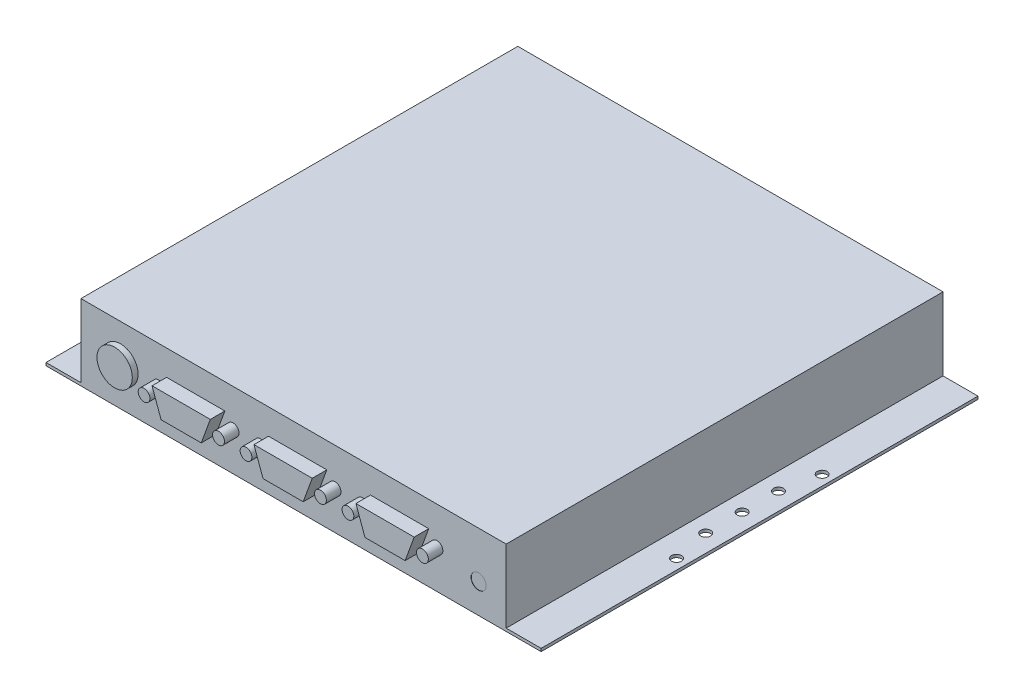
SolidWorks part; units mm, degrees
ref_plane "前视基准面" through (0, 0, 0) normal (0, 0, 1) x (1, 0, 0)
ref_plane "上视基准面" through (0, 0, 0) normal (0, 1, 0) x (1, 0, 0)
ref_plane "右视基准面" through (0, 0, 0) normal (1, 0, 0) x (0, 0, -1)
sketch "草图1" plane through (0, 0, 0) normal (0, 1, 0) x (1, 0, 0)
  line L1 (73, -75) -> (-73, -75)
  line L2 (73, -75) -> (73, 75)
  line L3 (73, 75) -> (-73, 75)
  line L4 (-73, -75) -> (-73, 75)
  line L5 (73, -75) -> (-73, 75) construction
  line L6 (73, 75) -> (-73, -75) construction
  point P0 (0, 0)
  dimension "D1" = 146
  dimension "D2" = 150
extrude "凸台-拉伸1" add sketch "草图1" along normal blind 26
sketch "草图2" plane through (0, 0, 0) normal (0, -1, 0) x (1, 0, 0)
  line L0 (-73, 75) -> (73, 75) construction
  line L1 (85, -75) -> (-85, -75)
  line L2 (85, -75) -> (85, 75)
  line L3 (85, 75) -> (-85, 75)
  line L4 (-85, -75) -> (-85, 75)
  line L5 (85, -75) -> (-85, 75) construction
  line L6 (85, 75) -> (-85, -75) construction
  point P0 (0, 0)
  dimension "D1" = 170
extrude "凸台-拉伸2" add sketch "草图2" against normal blind 1
hole_wizard "M3 间隙孔1" positions "草图3" profile "草图4" hole size "M3" standard "GB" end condition up to next
sketch "草图3" plane through (0, 1, 0) normal (0, 1, 0) x (1, 0, 0)
  line L0 (0, 0) -> (-85, 0) construction
  line L1 (-85, -75) -> (-85, 75) construction
  line L3 (0, 0) -> (0, 28.3891) construction
  line L6 (-73, -5.9635) -> (-85, -5.9635) construction
  line L7 (-73, -75) -> (-73, 75) construction
  point P0 (-81.5, 25)
  point P2 (-81.5, -25)
  point P4 (81.5, 25)
  point P6 (81.5, -25)
  point P19 (-79, 12.5)
  point P21 (-79, 0)
  point P23 (-79, -12.5)
  point P25 (79, -12.5)
  point P26 (79, 0)
  point P27 (79, 12.5)
  point P41 (-79, -5.9635)
  dimension "D1" = 163
  dimension "D2" = 50
  dimension "D3" = 25
sketch "草图4" plane through (-81.5, 1, -25) normal (1, 0, 0) x (0, 0, 1)
  line L0 (0, 0) -> (0, 1)
  line L1 (0, 1) -> (1.7, 1)
  line L2 (1.7, 1) -> (1.7, 0)
  line L5 (1.7, 0) -> (0, 0)
  line L11 (0, -6.35) -> (0, 107.95) construction
  dimension "通孔孔直径" = 3.4
  dimension "通孔孔深度" = 1
sketch "草图5" plane through (0, 0, 75) normal (0, 0, 1) x (1, 0, 0)
  circle A0 centre (-59.4316, 13.2786) radius 6.0638
extrude "凸台-拉伸3" add sketch "草图5" along normal blind 2
sketch "草图6" plane through (0, 0, 75) normal (0, 0, 1) x (1, 0, 0)
  line L0 (-43.5901, 17.274) -> (-23.5901, 17.274)
  line L1 (-23.5901, 17.274) -> (-26.6961, 8.7247)
  line L2 (-26.6961, 8.7247) -> (-40.484, 8.7247)
  line L3 (-40.484, 8.7247) -> (-43.5901, 17.274)
  line L4 (-33.5901, 8.7247) -> (-33.5901, 17.274) construction
  circle A0 centre (-46.3288, 13.1149) radius 2.0177
  circle A1 centre (-20.7695, 13.1149) radius 2.0399
  dimension "D1" = 20
extrude "凸台-拉伸4" add sketch "草图6" along normal blind 5
pattern_linear "阵列(线性)1" count 3 spacing 35 along (1, 0, 0) of "凸台-拉伸4"
sketch "草图7" plane through (0, 0, 75) normal (0, 0, 1) x (1, 0, 0)
  circle A0 centre (63.5175, 10.1213) radius 2.6001
extrude "切除-拉伸1" cut sketch "草图7" against normal blind 0.1
sketch "草图8" plane through (0, 0, -75) normal (0, 0, -1) x (-1, 0, 0)
  line L0 (2.6001, 20.5218) -> (-4.0859, 17.9957)
  line L1 (10.9577, 20.5218) -> (25.6299, 20.5218)
  line L2 (10.9577, 20.5218) -> (10.9577, 15.693)
  line L3 (10.9577, 15.693) -> (25.6299, 15.693)
  line L4 (25.6299, 20.5218) -> (25.6299, 15.693)
  line L5 (29.9015, 20.5218) -> (44.0165, 20.5218)
  line L6 (29.9015, 20.5218) -> (29.9015, 15.693)
  line L7 (29.9015, 15.693) -> (44.0165, 15.693)
  line L8 (44.0165, 20.5218) -> (44.0165, 15.693)
  line L9 (10.9577, 11.4213) -> (25.6299, 11.4213)
  line L10 (10.9577, 11.4213) -> (10.9577, 6.4068)
  line L11 (10.9577, 6.4068) -> (25.6299, 6.4068)
  line L12 (25.6299, 11.4213) -> (25.6299, 6.4068)
  line L13 (29.9015, 11.4213) -> (44.0165, 11.4213)
  line L14 (29.9015, 11.4213) -> (29.9015, 6.4068)
  line L15 (29.9015, 6.4068) -> (44.0165, 6.4068)
  line L16 (44.0165, 11.4213) -> (44.0165, 6.4068)
  line L17 (50.8883, 20.5218) -> (67.0462, 20.5218)
  line L18 (50.8883, 20.5218) -> (50.8883, 6.4068)
  line L19 (50.8883, 6.4068) -> (67.0462, 6.4068)
  line L20 (67.0462, 20.5218) -> (67.0462, 6.4068)
  line L22 (-4.0859, 17.9957) -> (-4.0859, 7.1543)
  line L24 (2.6001, 20.5218) -> (2.6001, 4.921)
  line L25 (2.6001, 4.921) -> (-4.0859, 7.1543)
extrude "切除-拉伸2" cut sketch "草图8" against normal blind 0.1
sketch "草图9" plane through (0, 0, -75) normal (0, 0, -1) x (-1, 0, 0)
  line L1 (-55.4789, 9.4233) -> (-35.4081, 9.4233)
  line L2 (-55.4789, 9.4233) -> (-55.4789, 6.8747)
  line L3 (-55.4789, 6.8747) -> (-35.4081, 6.8747)
  line L4 (-35.4081, 9.4233) -> (-35.4081, 6.8747)
  circle A0 centre (-64.6116, 7.9366) radius 1.2963
extrude "凸台-拉伸5" add sketch "草图9" along normal blind 0.1
